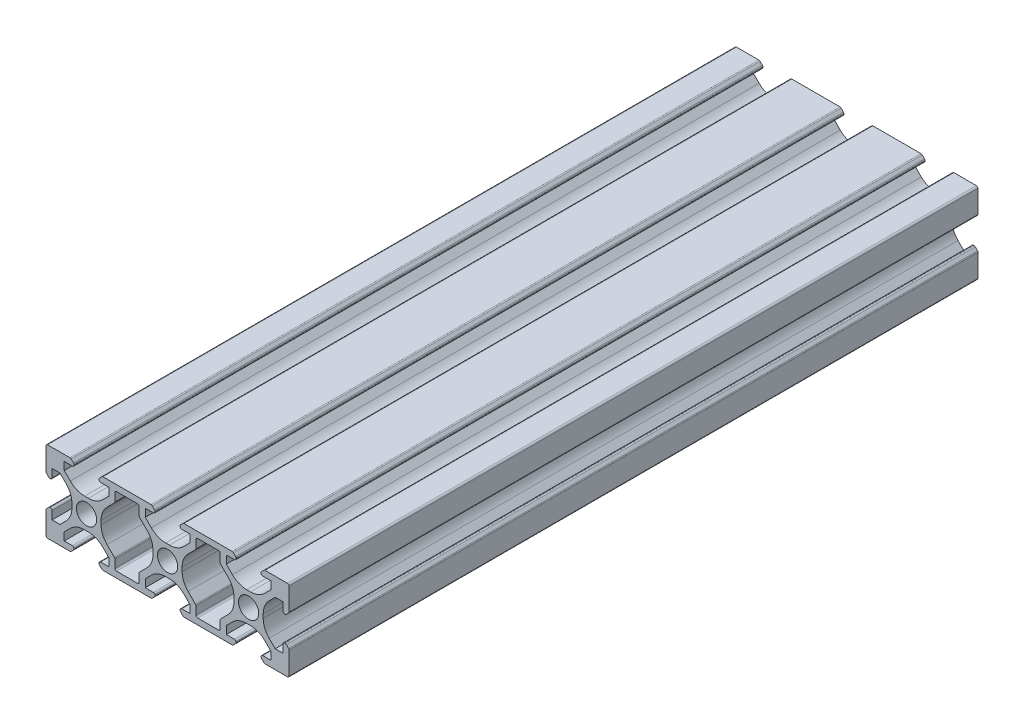
SolidWorks part; units mm, degrees
material "6063-T83"
ref_plane "Plano frontal" through (0, 0, 0) normal (0, 0, 1) x (1, 0, 0)
ref_plane "Plano superior" through (0, 0, 0) normal (0, 1, 0) x (1, 0, 0)
ref_plane "Plano direito" through (0, 0, 0) normal (1, 0, 0) x (0, 0, -1)
sketch "Esboço1" plane through (0, 0, 0) normal (0, 0, 1) x (1, 0, 0)
  line L0 (-9.0343, 3.1) -> (-8.9, 3.1)
  line L3 (-10, 10) -> (-4.0657, 10)
  line L5 (-10, -10) -> (10, 10) construction
  line L6 (-10, 10) -> (10, -10) construction
  line L7 (-8.5, 3.5) -> (-8.5, 5.5)
  line L8 (-10, 0) -> (10, 0) construction
  line L9 (0, 10) -> (0, -10) construction
  line L12 (-8.5, 5.5) -> (-6.5607, 5.5)
  line L15 (-6.5607, 5.5) -> (-5.0645, 4.0038)
  line L16 (-3.6, 0.4683) -> (-3.6, 0)
  line L17 (-0.4683, 3.6) -> (0, 3.6)
  line L18 (-5.5, 6.5607) -> (-4.0038, 5.0645)
  line L21 (-5.5, 8.5) -> (-5.5, 6.5607)
  line L24 (-3.5, 8.5) -> (-5.5, 8.5)
  line L25 (-3.1, 9.0343) -> (-3.1, 8.9)
  line L44 (-10, 4.0657) -> (-10, 10)
  line L45 (-9.8828, 3.7828) -> (-9.3172, 3.2172)
  line L46 (-3.7828, 9.8828) -> (-3.2172, 9.3172)
  line L47 (-3.6, 0) -> (-2.5, 0)
  line L48 (0, 3.6) -> (0, 2.5)
  arc A0 (-3.5, 8.5) -> (-3.1, 8.9) centre (-3.5, 8.9) ccw
  arc A1 (-3.7828, 9.8828) -> (-4.0657, 10) centre (-4.0657, 9.6) ccw
  arc A2 (-10, 4.0657) -> (-9.8828, 3.7828) centre (-9.6, 4.0657) ccw
  arc A3 (-8.5, 3.5) -> (-8.9, 3.1) centre (-8.9, 3.5) cw
  arc A4 (-3.2172, 9.3172) -> (-3.1, 9.0343) centre (-3.5, 9.0343) cw
  arc A5 (-9.3172, 3.2172) -> (-9.0343, 3.1) centre (-9.0343, 3.5) ccw
  arc A6 (-3.6, 0.4683) -> (-5.0645, 4.0038) centre (-8.6, 0.4683) ccw
  arc A7 (-4.0038, 5.0645) -> (-0.4683, 3.6) centre (-0.4683, 8.6) ccw
  circle A8 centre (0, 0) radius 2.5
  point P6 (-10, 3.1)
  point P28 (-3.1, 8.5)
  point P31 (-3.1, 10)
  point P33 (-3.9, 10)
  point P36 (-10, 3.9)
  point P39 (-8.5, 3.1)
  point P42 (-3.1, 9.2)
  point P45 (-9.2, 3.1)
  point P48 (-3.6, 2.5393)
  point P51 (-2.5393, 3.6)
  dimension "D5" = 10
  dimension "D9" = 0.4
  dimension "D10" = 0.4
  dimension "D11" = 5
  dimension "D12" = 5
  dimension "D13" = 5
  dimension "D1" = 6.9
  dimension "D2" = 1.5
  dimension "D3" = 3.6
  dimension "D4" = 1.5
  dimension "D6" = 2.4
  dimension "D7" = 3.6
  dimension "D8" = 45
extrude "Ressalto-extrusão1" add sketch "Esboço1" along normal blind 170
sketch "Esboço3" plane through (0, 0, 0) normal (1, 0, 0) x (0, 0, -1)
  line L0 (0, 0) -> (-1000, 0) construction
  dimension "D1" = 1000
pattern_circular "PadrãoCircular1" count 4 over 360 about axis through (0, 0, 0) along (0, 0, 1) of "Ressalto-extrusão1"
pattern_linear "Padrão linear1" count 3 spacing 20 along (1, 0, 0) of "Ressalto-extrusão1", "PadrãoCircular1"
sketch "Esboço4" plane through (0, 0, 0) normal (0, 0, -1) x (-1, 0, 0)
  line L0 (-13.4393, 5.5) -> (-13, 5.9393)
  line L1 (-13, 8.5) -> (-13, 5.9393)
  line L2 (-10, 10) -> (-10, -10) construction
  line L3 (-4.0657, 10) -> (-15.9343, 10) construction
  line L4 (-15.9343, -10) -> (-4.0657, -10) construction
  line L5 (-11.5, 5.5) -> (-13.4393, 5.5) construction
  line L6 (-14.5, 8.5) -> (-14.5, 6.5607) construction
  line L7 (-7, 8.5) -> (-7, 5.9393)
  line L8 (-6.5607, 5.5) -> (-7, 5.9393)
  line L9 (-13, 8.5) -> (-7, 8.5)
  line L10 (-20, 0) -> (0, 0) construction
  line L11 (-13, -8.5) -> (-7, -8.5)
  line L12 (-6.5607, -5.5) -> (-7, -5.9393)
  line L13 (-7, -8.5) -> (-7, -5.9393)
  line L14 (-13, -8.5) -> (-13, -5.9393)
  line L15 (-13.4393, -5.5) -> (-13, -5.9393)
  line L16 (-13.4393, 5.5) -> (-13.4393, -5.5)
  line L17 (-6.5607, -5.5) -> (-6.5607, 5.5)
  line L31 (-40, 0) -> (-20, 0) construction
  line L32 (-33.4393, 5.5) -> (-33, 5.9393) [skipped]
  line L33 (-33, 8.5) -> (-33, 5.9393) [skipped]
  line L34 (-27, 8.5) -> (-27, 5.9393) [skipped]
  line L35 (-26.5607, 5.5) -> (-27, 5.9393) [skipped]
  line L36 (-33, 8.5) -> (-27, 8.5) [skipped]
  line L37 (-33, -8.5) -> (-27, -8.5) [skipped]
  line L38 (-26.5607, -5.5) -> (-27, -5.9393) [skipped]
  line L39 (-27, -8.5) -> (-27, -5.9393) [skipped]
  line L40 (-33, -8.5) -> (-33, -5.9393) [skipped]
  line L41 (-33.4393, -5.5) -> (-33, -5.9393) [skipped]
  line L42 (-33.4393, 5.5) -> (-33.4393, -5.5) [skipped]
  line L43 (-26.5607, -5.5) -> (-26.5607, 5.5) [skipped]
  line L44 (-30, 10) -> (-30, -10) construction
  dimension "D1" = 45
  dimension "D2" = 1.5
  dimension "D3" = 1.5
  dimension "D4" = 2
extrude "Corte-extrusão1" cut sketch "Esboço4" against normal through all
pattern_linear "Padrão linear2" count 2 spacing 20 along (1, 0, 0) of "Corte-extrusão1"
fillet "Filete1" radius 0.4 16 edges at (13, -5.9393, 85) (13, -8.5, 85) (7, -8.5, 85) (7, -5.9393, 85) (7, 8.5, 85) (7, 5.9393, 85) (13, 8.5, 85) (13, 5.9393, 85) (27, -8.5, 85) (27, -5.9393, 85) (27, 8.5, 85) (27, 5.9393, 85) (33, 8.5, 85) (33, -8.5, 85) (33, -5.9393, 85) (33, 5.9393, 85)
fillet "Filete2" radius 0.4 4 edges at (-10, 10, 85) (50, -10, 85) (50, 10, 85) (-10, -10, 85)
ref_plane "Plane1" through (0, 0, 0) normal (0, 1, 0) x (1, 0, 0)
ref_plane "Plane2" through (20, 0, 0) normal (1, 0, 0) x (0, 0, -1)
ref_plane "Plane3" through (0, 0, 85) normal (0, 0, -1) x (-1, 0, 0)
